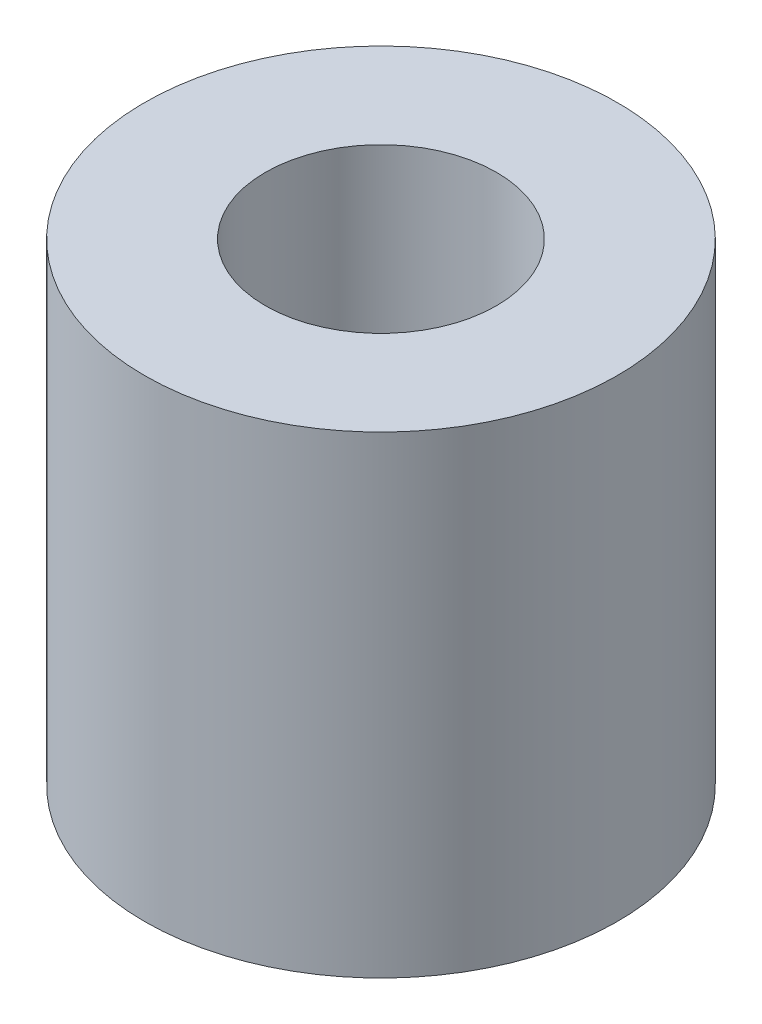
SolidWorks part; units mm, degrees
ref_plane "Front Plane" through (0, 0, 0) normal (0, 0, 1) x (1, 0, 0)
ref_plane "Top Plane" through (0, 0, 0) normal (0, 1, 0) x (1, 0, 0)
ref_plane "Right Plane" through (0, 0, 0) normal (1, 0, 0) x (0, 0, -1)
sketch "Sketch1" plane through (0, 0, 0) normal (0, 1, 0) x (1, 0, 0)
  circle A0 centre (0, 0) radius 2.25
  circle A2 centre (0, 0) radius 1.1
extrude "Boss-Extrude1" add sketch "Sketch1" along normal blind 4.5
